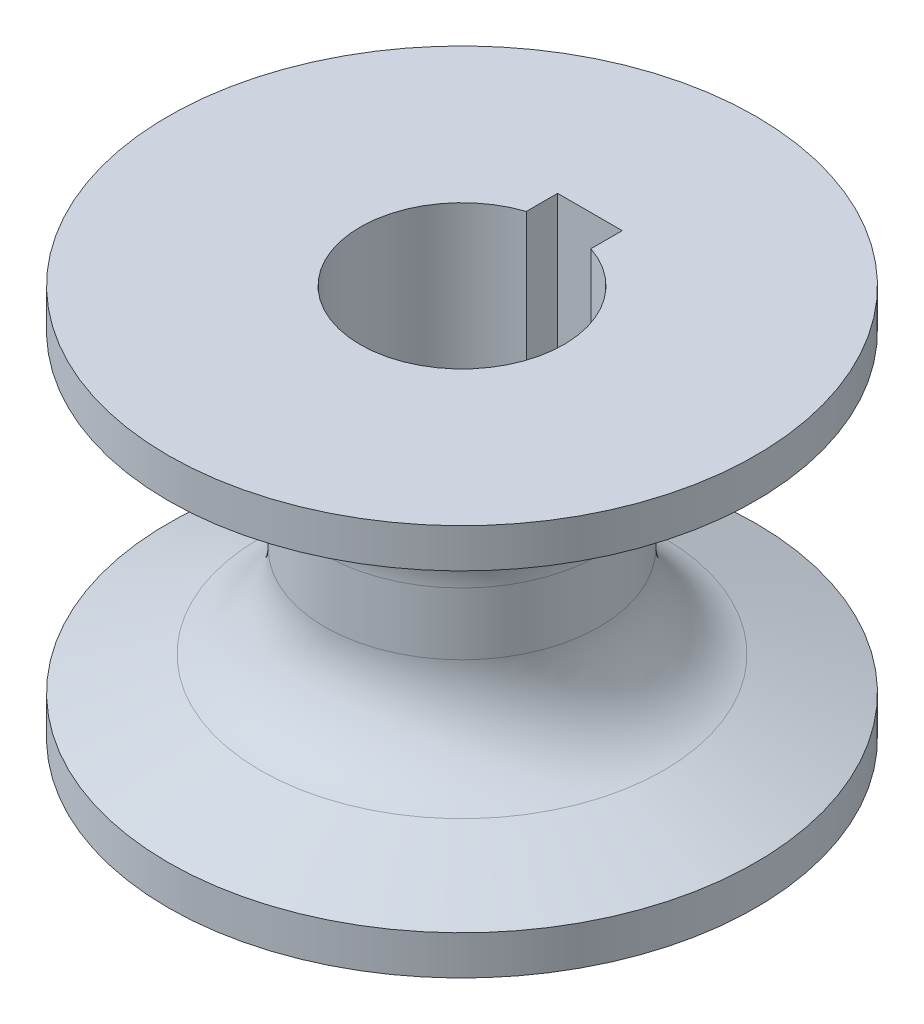
SolidWorks part; units mm, degrees
ref_plane "Plano frontal" through (0, 0, 0) normal (0, 0, 1) x (1, 0, 0)
ref_plane "Plano superior" through (0, 0, 0) normal (0, 1, 0) x (1, 0, 0)
ref_plane "Plano direito" through (0, 0, 0) normal (1, 0, 0) x (0, 0, -1)
sketch "Esboço2" plane through (0, 0, 0) normal (0, 1, 0) x (1, 0, 0)
  circle A0 centre (0, 0) radius 15
  dimension "D1" = 30
extrude "Ressalto-extrusão1" add sketch "Esboço2" along normal blind 20
hole_wizard "Furos-guia com Ø10.0mm1" positions "Esboço4" profile "Esboço5" hole size "Ø10.0" standard "Ansi Metric" end condition through all
sketch "Esboço4" plane through (0, 20, 0) normal (0, 1, 0) x (1, 0, 0)
  point P0 (0, 0)
sketch "Esboço5" plane through (0, 20, 0) normal (1, 0, 0) x (0, 0, 1)
  line L0 (0, 0) -> (0, 20)
  line L1 (0, 20) -> (5.2, 20)
  line L2 (5.2, 20) -> (5.2, 0)
  line L5 (5.2, 0) -> (0, 0)
  line L11 (0, -6.35) -> (0, 107.95) construction
  dimension "Thru Hole Dia." = 10.4
  dimension "Thru Hole Depth" = 20
sketch "Esboço6" plane through (0, 20, 0) normal (0, 1, 0) x (1, 0, 0)
  line L0 (-1.65, 4.9313) -> (-1.65, 6.5313)
  line L1 (-1.65, 6.5313) -> (1.65, 6.5313)
  line L2 (1.65, 6.5313) -> (1.65, 4.9313)
  circle A0 centre (0, 0) radius 5.2 construction
  arc A1 (-1.65, 4.9313) -> (1.65, 4.9313) centre (0, -0.2105) cw
  point P4 (0, 6.5313)
  dimension "D3" = 5.4
  dimension "D1" = 1.6
  dimension "D2" = 3.3
extrude "Corte-extrusão1" cut sketch "Esboço6" against normal through all
sketch "Esboço7" plane through (0, 0, 0) normal (0, 0, 1) x (1, 0, 0)
  line L1 (-15, 20) -> (-15, 0) construction
  line L4 (-15, 10) -> (15, 10) construction
  line L5 (15, 0) -> (15, 20) construction
  line L6 (0, 0) -> (0, 20) construction
  line L7 (15, 20) -> (-15, 20) construction
  line L8 (-15, 18) -> (-15, 2)
  line L9 (-15, 2) -> (-7, 4.9118)
  line L10 (-7, 15.0882) -> (-15, 18)
  line L11 (-7, 15.0882) -> (-7, 4.9118)
  point P1 (-7, 14.5782)
  dimension "D1" = 8
  dimension "D2" = 110
  dimension "D3" = 16
  dimension "D4" = 2
  dimension "D5" = 110
revolve "Corte-Revolução1" cut sketch "Esboço7" angle 360 about L6
fillet "Filete1" radius 5 2 edges at (0, 15.0882, -7) (0, 4.9118, -7)
